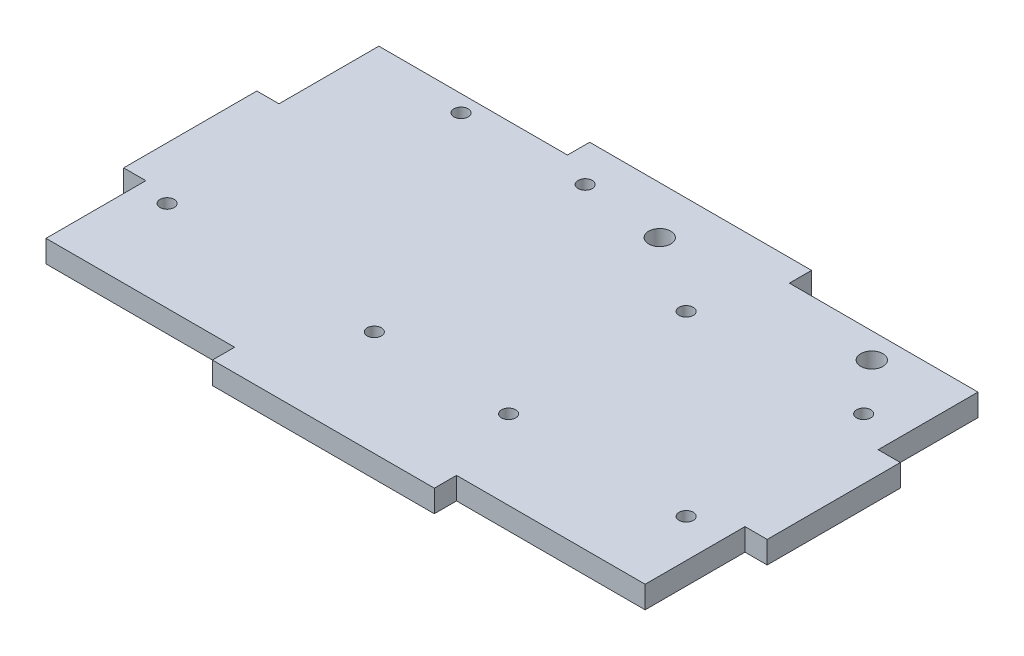
SolidWorks part; units mm, degrees
ref_plane "Front Plane" through (0, 0, 0) normal (0, 0, 1) x (1, 0, 0)
ref_plane "Top Plane" through (0, 0, 0) normal (0, 1, 0) x (1, 0, 0)
ref_plane "Right Plane" through (0, 0, 0) normal (1, 0, 0) x (0, 0, -1)
sketch "Sketch1" plane through (0, 0, 0) normal (0, 1, 0) x (1, 0, 0)
  line L1 (-72.5, -42.5) -> (72.5, -42.5)
  line L2 (-72.5, -42.5) -> (-72.5, 42.5)
  line L3 (-72.5, 42.5) -> (72.5, 42.5)
  line L4 (72.5, -42.5) -> (72.5, 42.5)
  line L5 (-72.5, -42.5) -> (72.5, 42.5) construction
  line L6 (-72.5, 42.5) -> (72.5, -42.5) construction
  point P0 (0, 0)
  dimension "D1" = 145
  dimension "D2" = 85
extrude "Boss-Extrude1" add sketch "Sketch1" along normal blind 5
sketch "Sketch2" plane through (0, 5, 0) normal (0, 1, 0) x (1, 0, 0)
  line L0 (72.5, -42.5) -> (72.5, 42.5) construction
  line L1 (-72.5, 42.5) -> (-25, 42.5)
  line L2 (-72.5, 42.5) -> (-72.5, 37.5)
  line L3 (-72.5, 37.5) -> (-25, 37.5)
  line L4 (72.5, 42.5) -> (72.5, 37.5)
  line L5 (-25, 42.5) -> (-25, 37.5)
  line L6 (25, 42.5) -> (25, 37.5)
  line L7 (25, 37.5) -> (72.5, 37.5)
  line L8 (25, 42.5) -> (72.5, 42.5)
  line L17 (-2.75, 0) -> (2.75, 0) construction
  line L18 (25, -42.5) -> (72.5, -42.5)
  line L19 (25, -42.5) -> (25, -37.5)
  line L20 (25, -37.5) -> (72.5, -37.5)
  line L21 (72.5, -42.5) -> (72.5, -37.5)
  line L22 (-72.5, -42.5) -> (-72.5, -37.5)
  line L23 (-72.5, -37.5) -> (-25, -37.5)
  line L24 (-25, -42.5) -> (-25, -37.5)
  line L25 (-72.5, -42.5) -> (-25, -42.5)
  dimension "D1" = 5
  dimension "D2" = 47.5
  dimension "D3" = 47.5
extrude "Cut-Extrude1" cut sketch "Sketch2" against normal blind 5
sketch "Sketch3" plane through (0, 5, 0) normal (0, 1, 0) x (1, 0, 0)
  line L0 (-25, -37.5) -> (-72.5, -37.5) construction
  line L1 (-72.5, 37.5) -> (-67.5, 37.5)
  line L2 (-72.5, 37.5) -> (-72.5, 15)
  line L3 (-72.5, -37.5) -> (-67.5, -37.5)
  line L4 (-67.5, 37.5) -> (-67.5, 15)
  line L5 (-67.5, -15) -> (-72.5, -15)
  line L6 (-67.5, 15) -> (-72.5, 15)
  line L7 (-67.5, -15) -> (-67.5, -37.5)
  line L8 (-72.5, -15) -> (-72.5, -37.5)
  line L9 (0, -2.75) -> (0, 2.75) construction
  line L10 (72.5, -15) -> (72.5, -37.5)
  line L11 (67.5, -15) -> (72.5, -15)
  line L12 (67.5, -15) -> (67.5, -37.5)
  line L13 (72.5, -37.5) -> (67.5, -37.5)
  line L14 (72.5, 37.5) -> (72.5, 15)
  line L15 (67.5, 15) -> (72.5, 15)
  line L16 (67.5, 37.5) -> (67.5, 15)
  line L17 (72.5, 37.5) -> (67.5, 37.5)
  dimension "D1" = 5
  dimension "D2" = 22.5
  dimension "D3" = 22.5
extrude "Cut-Extrude2" cut sketch "Sketch3" against normal blind 5
sketch "Sketch4" plane through (0, 5, 0) normal (0, 1, 0) x (1, 0, 0)
  line L0 (-45.22, 33.75) -> (-17.26, 33.75) construction
  line L1 (-67.5, -37.5) -> (-12.26, -37.5) construction
  line L2 (-67.5, -37.5) -> (-67.5, -18.77) construction
  line L3 (-67.5, -18.77) -> (-12.26, -18.77) construction
  line L4 (-12.26, -37.5) -> (-12.26, -18.77) construction
  line L5 (-67.5, -37.5) -> (-60.66, -37.5) construction
  line L6 (-67.5, -37.5) -> (-67.5, -17.06) construction
  line L7 (-67.5, -17.06) -> (-60.66, -17.06) construction
  line L8 (-60.66, -37.5) -> (-60.66, -17.06) construction
  line L9 (-67.5, 37.5) -> (-45.22, 37.5) construction
  line L10 (-67.5, 37.5) -> (-67.5, 33.75) construction
  line L11 (-67.5, 33.75) -> (-45.22, 33.75) construction
  line L12 (-45.22, 37.5) -> (-45.22, 33.75) construction
  circle A0 centre (-12.26, -18.77) radius 1.6
  circle A1 centre (-60.66, -17.06) radius 1.6
  circle A2 centre (-45.22, 33.75) radius 1.6
  circle A3 centre (-17.26, 33.75) radius 1.6
  dimension "D3" = 3.2
  dimension "D6" = 3.2
  dimension "D9" = 3.2
  dimension "D11" = 3.2
  dimension "D1" = 18.73
  dimension "D2" = 55.24
  dimension "D4" = 20.44
  dimension "D5" = 6.84
  dimension "D7" = 22.28
  dimension "D8" = 3.75
  dimension "D10" = 27.96
extrude "Cut-Extrude3" cut sketch "Sketch4" against normal blind 5
sketch "Sketch5" plane through (0, 5, 0) normal (0, 1, 0) x (1, 0, 0)
  line L0 (58.87, 20.37) -> (18.87, 20.37) construction
  line L1 (67.5, 37.5) -> (58.87, 37.5) construction
  line L2 (67.5, 37.5) -> (67.5, 20.37) construction
  line L3 (67.5, 20.37) -> (58.87, 20.37) construction
  line L4 (58.87, 37.5) -> (58.87, 20.37) construction
  line L5 (18.87, 20.37) -> (18.87, -19.63) construction
  circle A0 centre (58.87, 20.37) radius 1.6
  circle A1 centre (18.87, 20.37) radius 1.6
  circle A2 centre (18.87, -19.63) radius 1.6
  circle A3 centre (58.87, -19.63) radius 1.6
  dimension "D3" = 3.2
  dimension "D5" = 3.2
  dimension "D7" = 3.2
  dimension "D8" = 3.2
  dimension "D1" = 8.63
  dimension "D2" = 17.13
  dimension "D4" = 40
  dimension "D6" = 40
extrude "Cut-Extrude4" cut sketch "Sketch5" against normal blind 5
sketch "Sketch6" plane through (0, 5, 0) normal (0, 1, 0) x (1, 0, 0)
  line L0 (49.29, 31.79) -> (1.5, 31.79) construction
  line L1 (67.5, 37.5) -> (49.29, 37.5) construction
  line L2 (67.5, 37.5) -> (67.5, 31.79) construction
  line L3 (67.5, 31.79) -> (49.29, 31.79) construction
  line L4 (49.29, 37.5) -> (49.29, 31.79) construction
  circle A0 centre (49.29, 31.79) radius 2.5
  circle A1 centre (1.5, 31.79) radius 2.5
  dimension "D3" = 5
  dimension "D5" = 5
  dimension "D1" = 18.21
  dimension "D2" = 5.71
  dimension "D4" = 47.79
extrude "Cut-Extrude5" cut sketch "Sketch6" against normal blind 10
